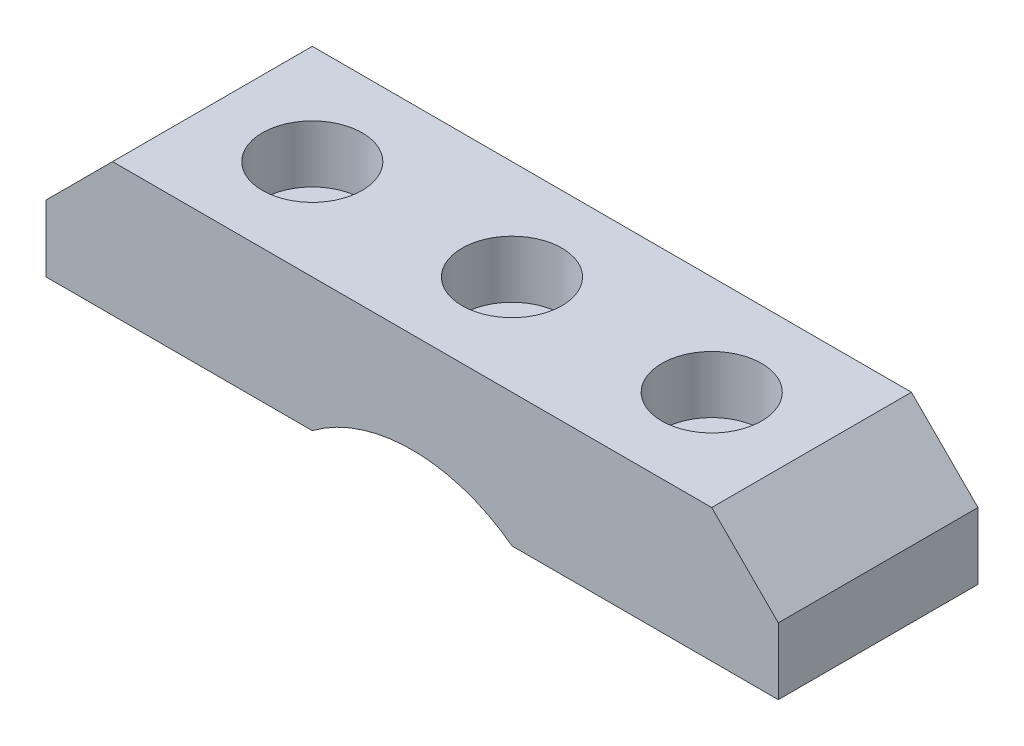
SolidWorks part; units mm, degrees
material "3.0205 (EN-AW 1200)"
ref_plane "Спереди" through (0, 0, 0) normal (0, 0, 1) x (1, 0, 0)
ref_plane "Сверху" through (0, 0, 0) normal (0, 1, 0) x (1, 0, 0)
ref_plane "Справа" through (0, 0, 0) normal (1, 0, 0) x (0, 0, -1)
sketch "Эскиз1" plane through (0, 0, 0) normal (0, 0, 1) x (1, 0, 0)
  line L0 (0, 0) -> (-44204.8898, 0) construction
  line L1 (0, 0) -> (0, 44204.8898) construction
  line L2 (-15, 20) -> (-55, 20)
  line L3 (-55, 20) -> (-55, 40)
  line L4 (-55, 40) -> (55, 40)
  line L5 (55, 40) -> (55, 20)
  line L6 (55, 20) -> (15, 20)
  arc A1 (15, 20) -> (-15, 20) centre (0, 0) ccw
  dimension "D1" = 25
  dimension "D2" = 30
  dimension "D3" = 20
  dimension "D4" = 110
extrude "Бобышка-Вытянуть1" add sketch "Эскиз1" along normal mid plane 30
sketch "Эскиз4" plane through (0, 40, 0) normal (0, 1, 0) x (1, 0, 0)
  line L0 (0, 0) -> (-50000, 0) construction
  line L1 (0, 0) -> (0, 50000) construction
  point P0 (0, 0)
  point P8 (-30, 0)
  point P10 (30, 0)
  dimension "D1" = 60
hole_wizard "Цековка для винта с внутренним шестигранником M81" positions "Эскиз4" profile "Эскиз3" counterbore size "M8" standard "DIN" end condition through all
sketch "Эскиз3" plane through (0, 40, 0) normal (1, 0, 0) x (0, 0, 1)
  line L0 (0, 0) -> (0, 20)
  line L1 (0, 20) -> (4.5, 20)
  line L3 (4.5, 20) -> (4.5, 8.6)
  line L4 (4.5, 8.6) -> (7.5, 8.6)
  line L5 (7.5, 8.6) -> (7.5, 0)
  line L7 (7.5, 0) -> (0, 0)
  line L11 (0, -6.35) -> (0, 107.95) construction
  dimension "Диаметр сквозного отверстия" = 9
  dimension "Глубина сквозного отверстия" = 20
  dimension "Диаметр цековки" = 15
  dimension "Глубина цековки" = 8.6
chamfer "Фаска1" distance 10 angle 45 2 edges at (-55, 40, 0) (55, 40, 0)
